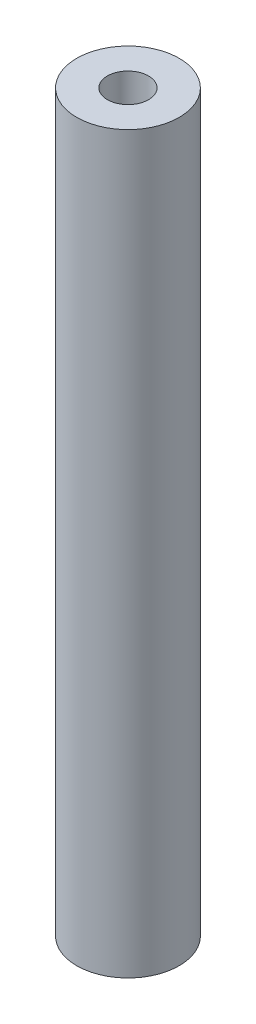
SolidWorks part; units mm, degrees
material "6061 Alloy"
ref_plane "Front" through (0, 0, 0) normal (0, 0, 1) x (1, 0, 0)
ref_plane "Top" through (0, 0, 0) normal (0, 1, 0) x (1, 0, 0)
ref_plane "Right" through (0, 0, 0) normal (1, 0, 0) x (0, 0, -1)
sketch "Sketch1" plane through (0, 0, 0) normal (0, 1, 0) x (1, 0, 0)
  circle A0 centre (0, 0) radius 6.35
  dimension "D1" = 12.7
extrude "Boss-Extrude1" add sketch "Sketch1" along normal blind 91.0844
hole_wizard "1/4-20 Tapped Hole1" positions "Sketch2" profile "Sketch3" tap size "1/4-20" standard "ANSI Inch"
sketch "Sketch2" plane through (0, 91.0844, 0) normal (0, 1, 0) x (1, 0, 0)
  point P0 (0, 0)
sketch "Sketch3" plane through (0, 91.0844, 0) normal (1, 0, 0) x (0, 0, 1)
  line L0 (0, 0) -> (0, 26.9338)
  line L1 (0, 26.9338) -> (2.5527, 25.4)
  line L2 (2.5527, 25.4) -> (2.5527, 0)
  line L5 (2.5527, 0) -> (0, 0)
  line L10 (0, 26.9338) -> (-2.5527, 25.4) construction
  line L11 (0, -6.35) -> (0, 107.95) construction
  dimension "Tap Drill Dia." = 5.1054
  dimension "Tap Drill Depth" = 25.4
  dimension "Drill Angle" = 118
cosmetic thread "Hole Thread1"
hole_wizard "1/4-20 Tapped Hole2" positions "Sketch4" profile "Sketch5" tap size "1/4-20" standard "ANSI Inch"
sketch "Sketch4" plane through (0, 0, 0) normal (0, -1, 0) x (-1, 0, 0)
  point P0 (0, 0)
sketch "Sketch5" plane through (0, 0, 0) normal (1, 0, 0) x (0, 0, -1)
  line L0 (0, 0) -> (0, 26.9338)
  line L1 (0, 26.9338) -> (2.5527, 25.4)
  line L2 (2.5527, 25.4) -> (2.5527, 0)
  line L5 (2.5527, 0) -> (0, 0)
  line L10 (0, 26.9338) -> (-2.5527, 25.4) construction
  line L11 (0, -6.35) -> (0, 107.95) construction
  dimension "Tap Drill Dia." = 5.1054
  dimension "Tap Drill Depth" = 25.4
  dimension "Drill Angle" = 118
cosmetic thread "Hole Thread2"
